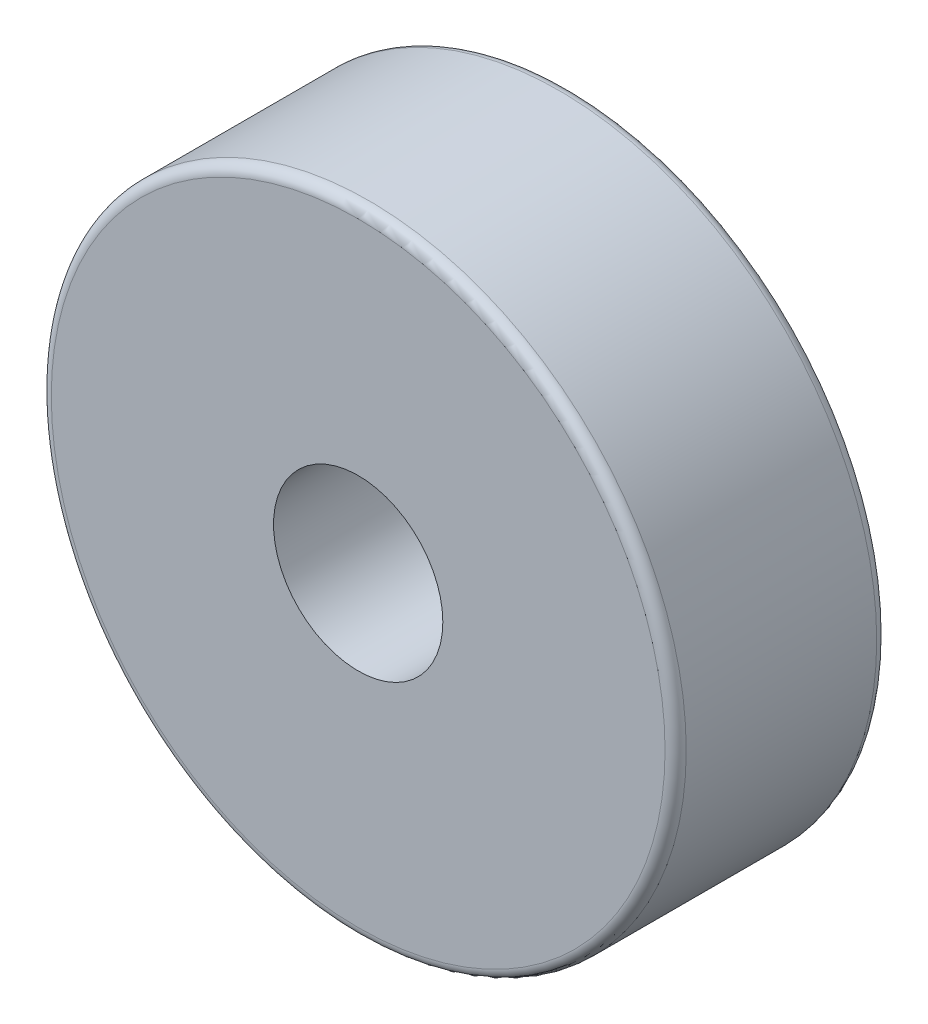
SolidWorks part; units mm, degrees
ref_plane "前视基准面" through (0, 0, 0) normal (0, 0, 1) x (1, 0, 0)
ref_plane "上视基准面" through (0, 0, 0) normal (0, 1, 0) x (1, 0, 0)
ref_plane "右视基准面" through (0, 0, 0) normal (1, 0, 0) x (0, 0, -1)
sketch "草图1" plane through (0, 0, 0) normal (0, 0, 1) x (1, 0, 0)
  circle A0 centre (0, 0) radius 4
  circle A1 centre (0, 0) radius 15
  dimension "D1" = 8
  dimension "D2" = 30
extrude "凸台-拉伸1" add sketch "草图1" along normal blind 10
fillet "圆角1" radius 0.5 2 edges at (15, 0, 0) (15, 0, 10)
